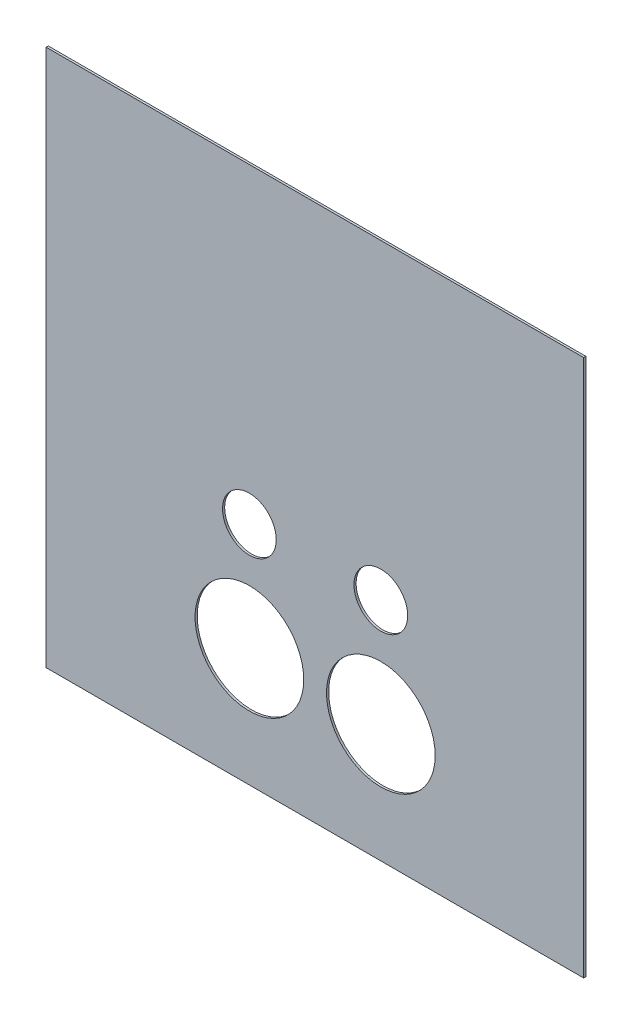
SolidWorks part; units mm, degrees
material "1060 Alloy"
ref_plane "Front Plane" through (0, 0, 0) normal (0, 0, 1) x (1, 0, 0)
ref_plane "Top Plane" through (0, 0, 0) normal (0, 1, 0) x (1, 0, 0)
ref_plane "Right Plane" through (0, 0, 0) normal (1, 0, 0) x (0, 0, -1)
sketch "Sketch2" plane through (0, 0, 0) normal (0, 0, 1) x (1, 0, 0)
  line L1 (-130.1775, 329.8817) -> (369.8225, 329.8817)
  line L2 (-130.1775, 329.8817) -> (-130.1775, -170.1183)
  line L3 (-130.1775, -170.1183) -> (369.8225, -170.1183)
  line L4 (369.8225, 329.8817) -> (369.8225, -170.1183)
  dimension "D1" = 500
  dimension "D2" = 500
extrude "Boss-Extrude2" add sketch "Sketch2" along normal blind 2 contours L2 L3 L4 L1
sketch "Sketch5" plane through (0, 0, 2) normal (0, 0, 1) x (1, 0, 0)
  line L0 (-130.1775, -170.1183) -> (369.8225, -170.1183) construction
  line L1 (-1.3075, 0.1817) -> (118.9925, 0.1817)
  line L2 (-1.3075, 0.1817) -> (-1.3075, -120.1183)
  line L3 (-1.3075, -120.1183) -> (118.9925, -120.1183)
  line L4 (118.9925, 0.1817) -> (118.9925, -120.1183)
  line L5 (-1.3075, 0.1817) -> (118.9925, -120.1183) construction
  line L6 (-1.3075, -120.1183) -> (118.9925, 0.1817) construction
  line L7 (120.9925, 0.1817) -> (241.2925, 0.1817)
  line L8 (120.9925, 0.1817) -> (120.9925, -120.1183)
  line L9 (120.9925, -120.1183) -> (241.2925, -120.1183)
  line L10 (241.2925, 0.1817) -> (241.2925, -120.1183)
  line L11 (120.9925, 0.1817) -> (241.2925, -120.1183) construction
  line L12 (120.9925, -120.1183) -> (241.2925, 0.1817) construction
  line L13 (-130.1775, 329.8817) -> (-130.1775, -170.1183) construction
  circle A0 centre (58.8425, -59.9683) radius 50.55
  circle A1 centre (181.1425, -59.9683) radius 50.55
  dimension "D1" = 101.1
  dimension "D2" = 101.1
  dimension "D3" = 2
  dimension "D4" = 0
  dimension "D5" = 60.15
  dimension "D6" = 50
  dimension "D7" = 0
  dimension "D8" = 128.87
extrude "Cut-Extrude1" cut sketch "Sketch5" against normal blind 2 contours A0 | A1
sketch "Sketch6" plane through (0, 0, 2) normal (0, 0, 1) x (1, 0, 0)
  circle A0 centre (181.1425, 40.0317) radius 25
  circle A1 centre (58.8425, 40.0317) radius 25
  circle A2 centre (58.8425, -59.9683) radius 50.55 construction
  circle A3 centre (181.1425, -59.9683) radius 50.55 construction
  point P4 (53.0114, 65.7177)
  point P7 (0, 0)
  point P10 (58.8425, 39.882)
  point P11 (181.1425, 40.0317)
  dimension "D1" = 50
  dimension "D2" = 50
  dimension "D3" = 100
  dimension "D4" = 100
  dimension "D5" = 50
extrude "Cut-Extrude2" cut sketch "Sketch6" against normal blind 10
